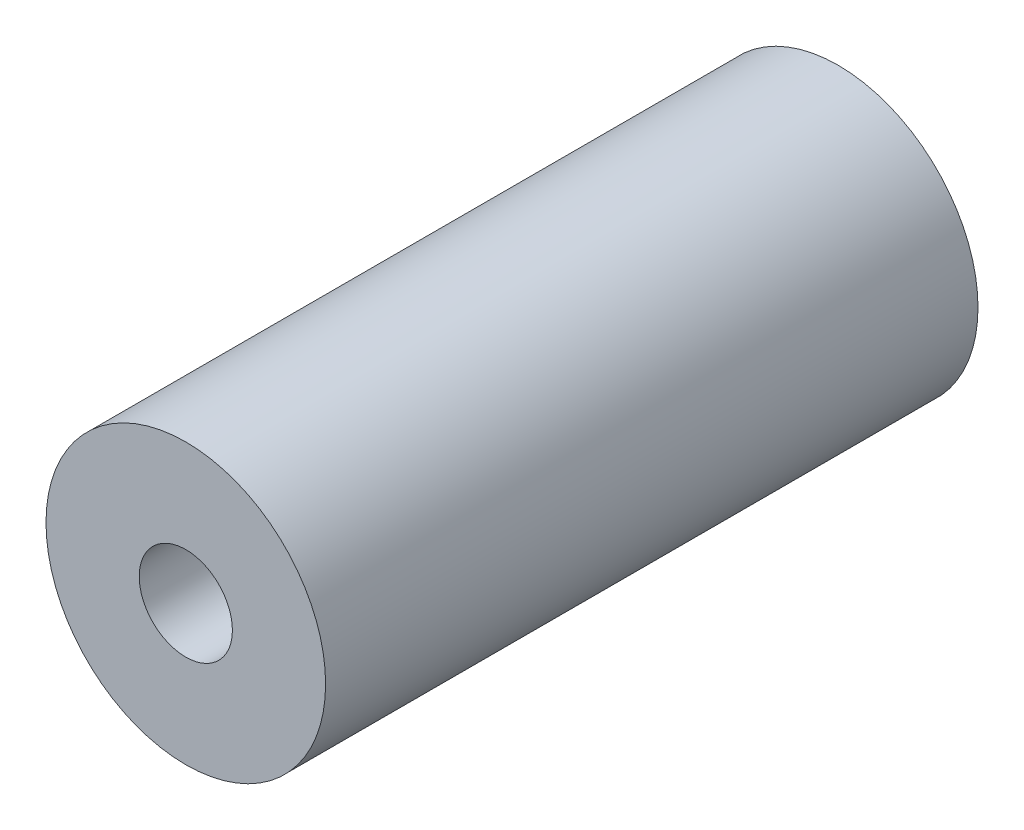
SolidWorks part; units mm, degrees
ref_plane "Front Plane" through (0, 0, 0) normal (0, 0, 1) x (1, 0, 0)
ref_plane "Top Plane" through (0, 0, 0) normal (0, 1, 0) x (1, 0, 0)
ref_plane "Right Plane" through (0, 0, 0) normal (1, 0, 0) x (0, 0, -1)
sketch "Sketch1" plane through (0, 0, 0) normal (0, 0, 1) x (1, 0, 0)
  circle A0 centre (0, 0) radius 3
  circle A1 centre (0, 0) radius 1
  dimension "D1" = 6
  dimension "D2" = 2
extrude "Boss-Extrude1" add sketch "Sketch1" along normal blind 14
